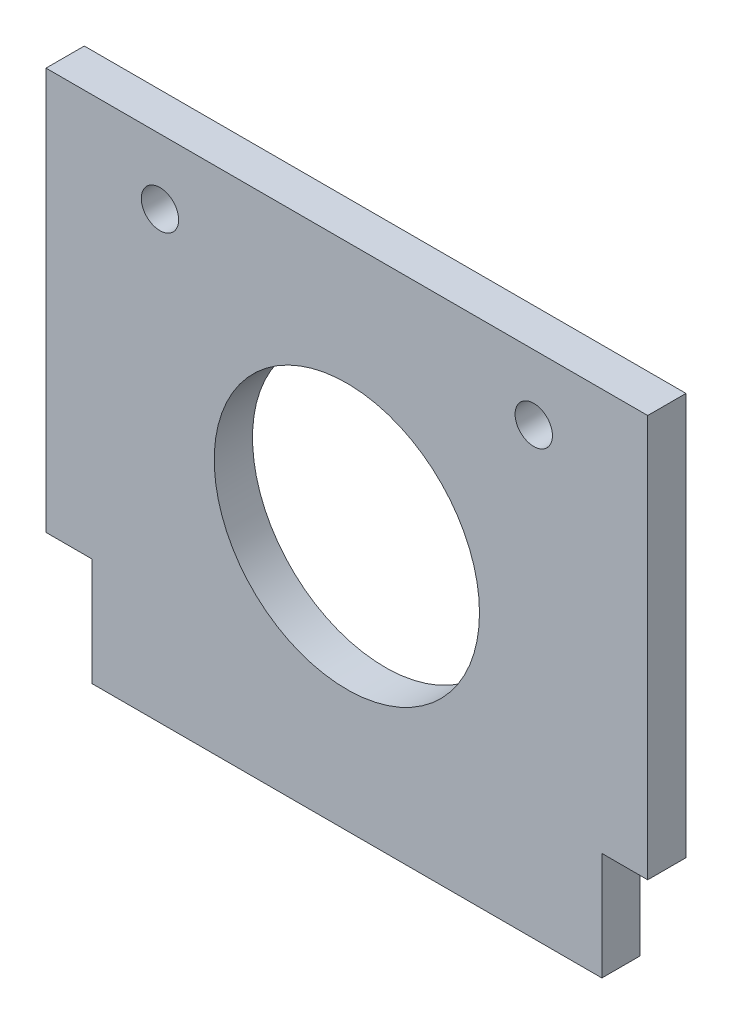
SolidWorks part; units mm, degrees
ref_plane "Front Plane" through (0, 0, 0) normal (0, 0, 1) x (1, 0, 0)
ref_plane "Top Plane" through (0, 0, 0) normal (0, 1, 0) x (1, 0, 0)
ref_plane "Right Plane" through (0, 0, 0) normal (1, 0, 0) x (0, 0, -1)
sketch "Sketch1" plane through (0, 0, 0) normal (0, 0, 1) x (1, 0, 0)
  line L0 (0, 42.3) -> (42.3, 0) construction
  line L1 (0, 0) -> (42.3, 0)
  line L2 (0, 0) -> (0, 8.9501)
  line L3 (0, 42.3) -> (42.3, 42.3)
  line L4 (42.3, 0) -> (42.3, 8.9501)
  line L5 (42.3, 42.3) -> (0, 0) construction
  line L6 (21.15, 21.15) -> (42.25, 21.15) construction
  line L7 (42.3, 8.9501) -> (46.1, 8.9501)
  line L8 (0, 8.9501) -> (-3.8, 8.9501)
  line L9 (0, 42.3) -> (-3.8, 42.3)
  line L10 (-3.8, 42.3) -> (-3.8, 8.9501)
  line L11 (42.3, 42.3) -> (46.1, 42.3)
  line L12 (46.1, 42.3) -> (46.1, 8.9501)
  circle A0 centre (21.15, 21.15) radius 11
  circle A4 centre (36.65, 36.9) radius 1.55 construction
  circle A11 centre (5.65, 36.9) radius 1.55 construction
  circle A14 centre (36.65, 36.9) radius 1.55
  circle A15 centre (5.65, 36.9) radius 1.55
  dimension "D3" = 22
  dimension "D1" = 42.3
  dimension "D2" = 42.3
  dimension "D4" = 12.2
  dimension "D5" = 3.8
  dimension "D6" = 3.8
  dimension "D7" = 42.3
extrude "Boss-Extrude1" add sketch "Sketch1" along normal blind 3.175
